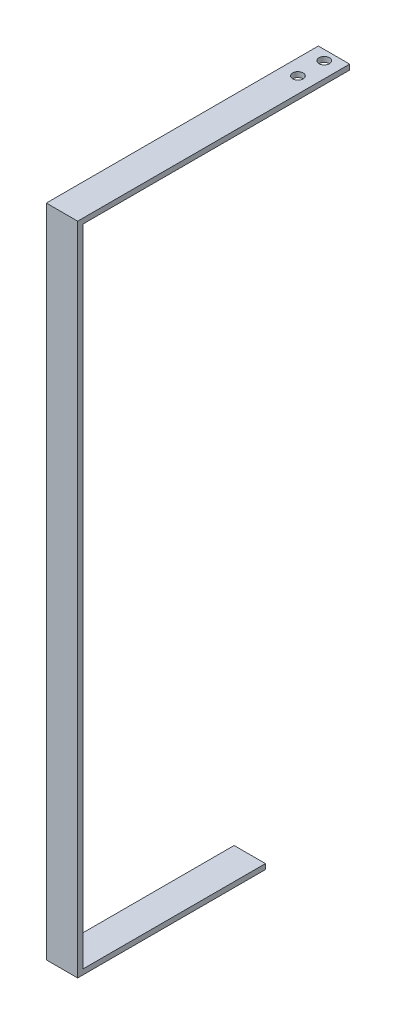
SolidWorks part; units mm, degrees
ref_plane "Alzado" through (0, 0, 0) normal (0, 0, 1) x (1, 0, 0)
ref_plane "Planta" through (0, 0, 0) normal (0, 1, 0) x (1, 0, 0)
ref_plane "Vista lateral" through (0, 0, 0) normal (1, 0, 0) x (0, 0, -1)
sketch "Croquis1" plane through (0, 0, 0) normal (0, 0, 1) x (1, 0, 0)
  line L1 (19.05, -3.155) -> (-19.05, -3.155)
  line L2 (19.05, -3.155) -> (19.05, 3.155)
  line L3 (19.05, 3.155) -> (-19.05, 3.155)
  line L4 (-19.05, -3.155) -> (-19.05, 3.155)
  line L5 (19.05, -3.155) -> (-19.05, 3.155) construction
  line L6 (19.05, 3.155) -> (-19.05, -3.155) construction
  point P0 (0, 0)
  dimension "D1" = 38.1
  dimension "D2" = 6.31
extrude "Saliente-Extruir1" add sketch "Croquis1" along normal blind 228.31
sketch "Croquis2" plane through (0, 3.155, 0) normal (0, 1, 0) x (1, 0, 0)
  line L0 (-19.05, -228.31) -> (19.05, -228.31)
  line L1 (19.05, -228.31) -> (19.05, -222)
  line L2 (19.05, -228.31) -> (19.05, 0) construction
  line L3 (19.05, -222) -> (-19.05, -222)
  line L4 (-19.05, -228.31) -> (-19.05, 0) construction
  line L5 (-19.05, -222) -> (-19.05, -228.31)
  dimension "D1" = 6.31
extrude "Saliente-Extruir2" add sketch "Croquis2" along normal blind 790.55
sketch "Croquis3" plane through (0, 0, 222) normal (0, 0, -1) x (-1, 0, 0)
  line L0 (19.05, 793.705) -> (19.05, 787.395)
  line L1 (19.05, 793.705) -> (19.05, 3.155) construction
  line L2 (19.05, 787.395) -> (-19.05, 787.395)
  line L3 (-19.05, 793.705) -> (-19.05, 3.155) construction
  line L4 (-19.05, 787.395) -> (-19.05, 793.705)
  line L5 (-19.05, 793.705) -> (19.05, 793.705)
  dimension "D1" = 6.31
extrude "Saliente-Extruir3" add sketch "Croquis3" along normal blind 324.39
sketch "Croquis4" plane through (0, 793.705, 0) normal (0, 1, 0) x (1, 0, 0)
  circle A0 centre (0, 90.4978) radius 6.35
  circle A1 centre (0, 58.4978) radius 6.35
extrude "Cortar-Extruir1" cut sketch "Croquis4" against normal blind 6.31
